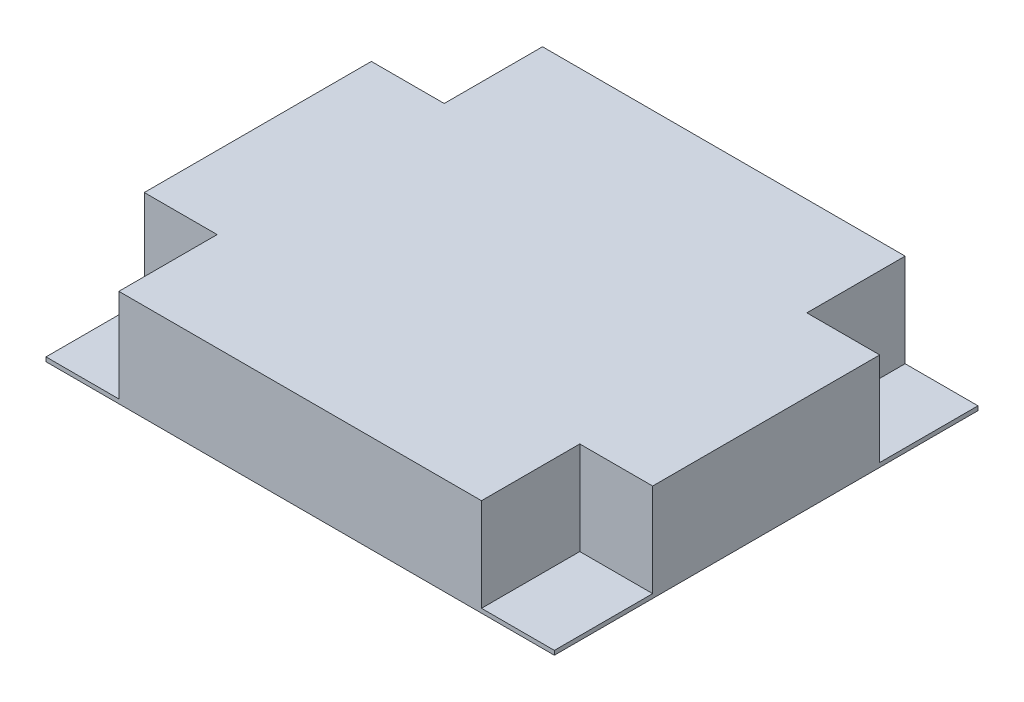
SolidWorks part; units mm, degrees
ref_plane "Front Plane" through (0, 0, 0) normal (0, 0, 1) x (1, 0, 0)
ref_plane "Top Plane" through (0, 0, 0) normal (0, 1, 0) x (1, 0, 0)
ref_plane "Right Plane" through (0, 0, 0) normal (1, 0, 0) x (0, 0, -1)
sketch "Sketch1" plane through (0, 0, 0) normal (0, 1, 0) x (1, 0, 0)
  line L1 (0, 0) -> (600, 0)
  line L2 (0, 0) -> (0, -500)
  line L3 (0, -500) -> (600, -500)
  line L4 (600, 0) -> (600, -500)
extrude "Boss-Extrude1" add sketch "Sketch1" along normal blind 115 contours L2 L1 L4 L3
sketch "Sketch3" plane through (0, 115, 0) normal (0, 1, 0) x (1, 0, 0)
  line L0 (300, -500) -> (300, 0) construction
  line L1 (0, -500) -> (86, -500)
  line L2 (0, -500) -> (0, -384)
  line L3 (0, -384) -> (86, -384)
  line L4 (86, -500) -> (86, -384)
  line L5 (0, -500) -> (600, -500) construction
  line L6 (0, 0) -> (600, 0) construction
  line L7 (0, -250) -> (600, -250) construction
  line L10 (0, 0) -> (0, -500) construction
  line L11 (600, 0) -> (600, -500) construction
  line L12 (0, -116) -> (86, -116)
  line L13 (86, 0) -> (86, -116)
  line L14 (0, 0) -> (86, 0)
  line L15 (0, 0) -> (0, -116)
  line L16 (600, 0) -> (600, -116)
  line L17 (600, 0) -> (514, 0)
  line L18 (514, 0) -> (514, -116)
  line L19 (600, -116) -> (514, -116)
  line L20 (600, -500) -> (514, -500)
  line L21 (514, -500) -> (514, -384)
  line L22 (600, -384) -> (514, -384)
  line L23 (600, -500) -> (600, -384)
extrude "Cut-Extrude1" cut sketch "Sketch3" against normal blind 110
sketch "Sketch4" plane through (0, 115, 0) normal (0, 1, 0) x (1, 0, 0)
  line L0 (0, -250) -> (600, -250) construction
  line L1 (0, -116) -> (0, -384) construction
  line L2 (600, -116) -> (600, -384) construction
  line L4 (128.8172, -51.0475) -> (471.1828, -51.0475)
  line L5 (128.8172, -51.0475) -> (128.8172, -448.9525)
  line L6 (128.8172, -448.9525) -> (471.1828, -448.9525)
  line L7 (471.1828, -51.0475) -> (471.1828, -448.9525)
  line L8 (128.8172, -51.0475) -> (471.1828, -448.9525) construction
  line L9 (128.8172, -448.9525) -> (471.1828, -51.0475) construction
  line L10 (251.7449, -193.9168) -> (348.2551, -193.9168)
  line L11 (251.7449, -193.9168) -> (251.7449, -306.0832)
  line L12 (251.7449, -306.0832) -> (348.2551, -306.0832)
  line L13 (348.2551, -193.9168) -> (348.2551, -306.0832)
  line L14 (251.7449, -193.9168) -> (348.2551, -306.0832) construction
  line L15 (251.7449, -306.0832) -> (348.2551, -193.9168) construction
  point P6 (300, -250)
  point P11 (300, -250)
